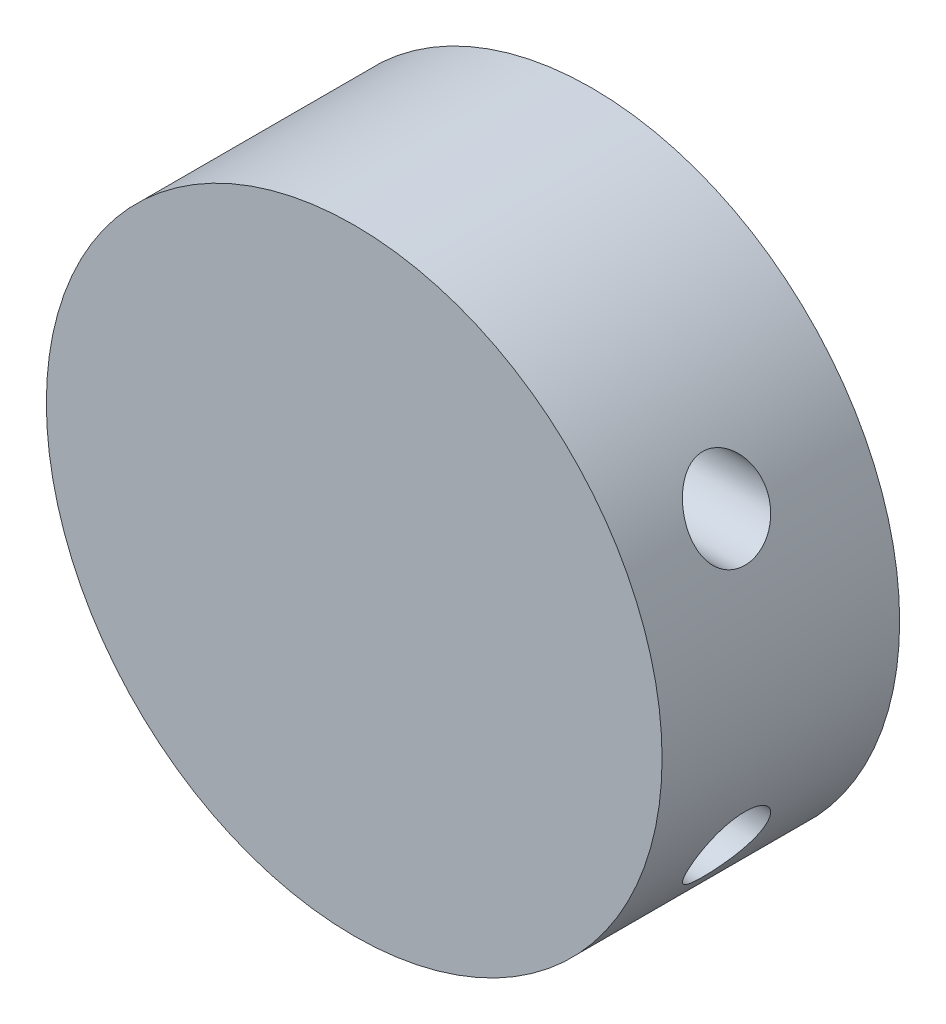
SolidWorks part; units mm, degrees
ref_plane "Ebene vorne" through (0, 0, 0) normal (0, 0, 1) x (1, 0, 0)
ref_plane "Ebene oben" through (0, 0, 0) normal (0, 1, 0) x (1, 0, 0)
ref_plane "Ebene rechts" through (0, 0, 0) normal (1, 0, 0) x (0, 0, -1)
sketch "Skizze1" plane through (0, 0, 0) normal (0, 0, 1) x (1, 0, 0)
  circle A0 centre (0, 0) radius 31.75
  dimension "D1" = 63.5
extrude "Lidar Base" add sketch "Skizze1" along normal blind 24.5
ref_plane "Ebene1" through (20, 0, 0) normal (1, 0, 0) x (0, 0, -1)
sketch "Skizze2" plane through (20, 0, 0) normal (1, 0, 0) x (0, 0, -1)
  line L0 (-14, 31.75) -> (-14, -31.75) construction
  line L1 (0, 31.75) -> (-24.5, 31.75) construction
  line L2 (-24.5, -31.75) -> (0, -31.75) construction
  line L3 (0, 0) -> (-24.5, 0) construction
  line L4 (-24.5, 31.75) -> (-24.5, -31.75) construction
  circle A0 centre (-14, 15) radius 4
  circle A1 centre (-14, -15) radius 4
  dimension "D1" = 8
  dimension "D2" = 14
  dimension "D3" = 30
extrude "Sensor Cut" cut sketch "Skizze2" along normal through all
